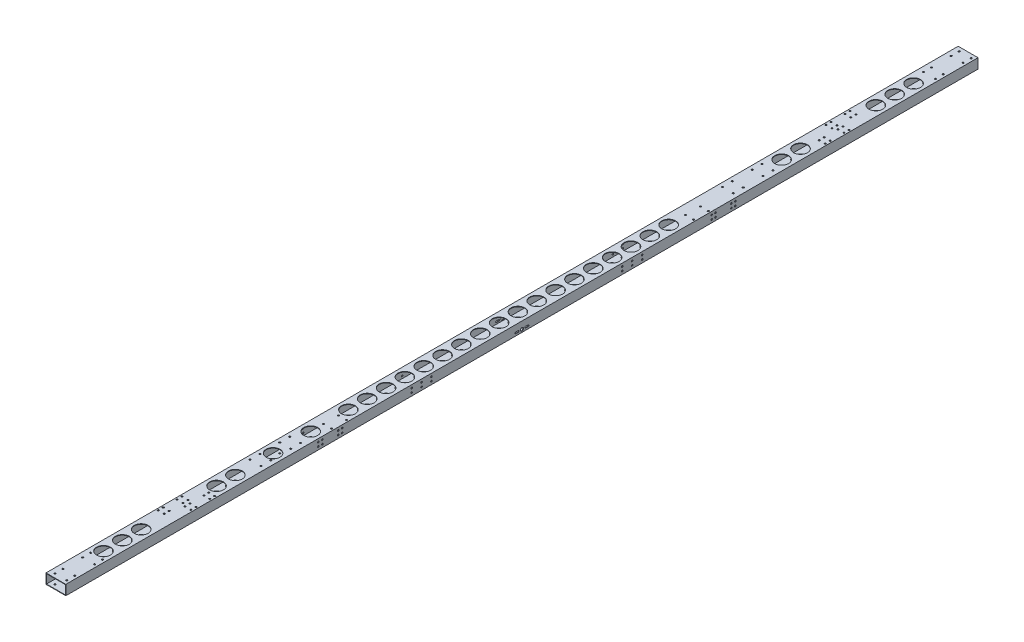
SolidWorks part; units mm, degrees
material "1100-H18 棒材(SS)"
ref_plane "前视基准面" through (0, 0, 0) normal (0, 0, 1) x (1, 0, 0)
ref_plane "上视基准面" through (0, 0, 0) normal (0, 1, 0) x (1, 0, 0)
ref_plane "右视基准面" through (0, 0, 0) normal (1, 0, 0) x (0, 0, -1)
other "Configuration Table"
sketch "草图1" plane through (0, 0, 0) normal (0, 0, 1) x (1, 0, 0)
  line L1 (0, 0) -> (40, 0)
  line L2 (0, 0) -> (0, 20)
  line L3 (0, 20) -> (40, 20)
  line L4 (40, 0) -> (40, 20)
  line L5 (1, 1) -> (39, 1)
  line L6 (1, 1) -> (1, 19)
  line L7 (1, 19) -> (39, 19)
  line L8 (39, 1) -> (39, 19)
  dimension "D1" = 40
  dimension "D2" = 20
  dimension "D3" = 1
  dimension "D4" = 1
  dimension "D5" = 1
  dimension "D6" = 1
extrude "凸台-拉伸1" add sketch "草图1" along normal blind 1840
sketch "草图2" plane through (0, 0, 0) normal (0, -1, 0) x (1, 0, 0)
  circle A9 centre (34, 8) radius 1.6
  circle A10 centre (34, 8) radius 1.6
  circle A11 centre (34, 24) radius 1.6
  circle A12 centre (34, 24) radius 1.6
  circle A13 centre (34, 64) radius 1.6
  circle A14 centre (34, 64) radius 1.6
  circle A15 centre (34, 80) radius 1.6
  circle A16 centre (34, 80) radius 1.6
  circle A17 centre (10, 64) radius 1.6
  circle A18 centre (10, 64) radius 1.6
  circle A19 centre (10, 80) radius 1.6
  circle A20 centre (10, 80) radius 1.6
  circle A21 centre (10, 24) radius 1.6
  circle A22 centre (10, 24) radius 1.6
  circle A23 centre (10, 8) radius 1.6
  circle A24 centre (10, 8) radius 1.6
  circle A39 centre (4, 232.5064) radius 1.6
  circle A40 centre (4, 232.5064) radius 1.6
  circle A41 centre (16, 270.5064) radius 1.6
  circle A42 centre (16, 270.5064) radius 1.6
  circle A43 centre (4, 270.5064) radius 1.6
  circle A44 centre (4, 270.5064) radius 1.6
  circle A45 centre (16, 222.5064) radius 1.6
  circle A46 centre (16, 222.5064) radius 1.6
  circle A47 centre (4, 222.5064) radius 1.6
  circle A48 centre (4, 222.5064) radius 1.6
  circle A49 centre (16, 260.5064) radius 1.6
  circle A50 centre (16, 260.5064) radius 1.6
  circle A51 centre (4, 260.5064) radius 1.6
  circle A52 centre (4, 260.5064) radius 1.6
  circle A53 centre (16, 232.5064) radius 1.6
  circle A54 centre (16, 232.5064) radius 1.6
  circle A61 centre (8, 483.5) radius 1.6
  circle A62 centre (8, 483.5) radius 1.6
  circle A63 centre (30, 483.5) radius 1.6
  circle A64 centre (30, 483.5) radius 1.6
  circle A65 centre (30, 463.5) radius 1.6
  circle A66 centre (30, 463.5) radius 1.6
  circle A67 centre (30, 423.5) radius 1.6
  circle A68 centre (30, 423.5) radius 1.6
  circle A69 centre (8, 403.5) radius 1.6
  circle A70 centre (8, 403.5) radius 1.6
  circle A71 centre (30, 403.5) radius 1.6
  circle A72 centre (30, 403.5) radius 1.6
  circle A75 centre (8, 423.5) radius 1.6
  circle A76 centre (8, 423.5) radius 1.6
  circle A77 centre (8, 463.5) radius 1.6
  circle A78 centre (8, 463.5) radius 1.6
  circle A81 centre (8, 1436.5) radius 1.6
  circle A82 centre (8, 1436.5) radius 1.6
  circle A83 centre (30, 1436.5) radius 1.6
  circle A84 centre (30, 1436.5) radius 1.6
  circle A85 centre (30, 1416.5) radius 1.6
  circle A86 centre (30, 1416.5) radius 1.6
  circle A87 centre (30, 1376.5) radius 1.6
  circle A88 centre (30, 1376.5) radius 1.6
  circle A89 centre (8, 1356.5) radius 1.6
  circle A90 centre (8, 1356.5) radius 1.6
  circle A91 centre (30, 1356.5) radius 1.6
  circle A92 centre (30, 1356.5) radius 1.6
  circle A95 centre (8, 1376.5) radius 1.6
  circle A96 centre (8, 1376.5) radius 1.6
  circle A97 centre (8, 1416.5) radius 1.6
  circle A98 centre (8, 1416.5) radius 1.6
  circle A103 centre (4, 1607.4936) radius 1.6
  circle A104 centre (4, 1607.4936) radius 1.6
  circle A105 centre (16, 1569.4936) radius 1.6
  circle A106 centre (16, 1569.4936) radius 1.6
  circle A107 centre (4, 1569.4936) radius 1.6
  circle A108 centre (4, 1569.4936) radius 1.6
  circle A109 centre (16, 1617.4936) radius 1.6
  circle A110 centre (16, 1617.4936) radius 1.6
  circle A111 centre (4, 1617.4936) radius 1.6
  circle A112 centre (4, 1617.4936) radius 1.6
  circle A113 centre (16, 1579.4936) radius 1.6
  circle A114 centre (16, 1579.4936) radius 1.6
  circle A115 centre (4, 1579.4936) radius 1.6
  circle A116 centre (4, 1579.4936) radius 1.6
  circle A117 centre (16, 1607.4936) radius 1.6
  circle A118 centre (16, 1607.4936) radius 1.6
  circle A127 centre (34, 1832) radius 1.6
  circle A128 centre (34, 1832) radius 1.6
  circle A129 centre (34, 1816) radius 1.6
  circle A130 centre (34, 1816) radius 1.6
  circle A131 centre (34, 1776) radius 1.6
  circle A132 centre (34, 1776) radius 1.6
  circle A133 centre (34, 1760) radius 1.6
  circle A134 centre (34, 1760) radius 1.6
  circle A135 centre (10, 1776) radius 1.6
  circle A136 centre (10, 1776) radius 1.6
  circle A137 centre (10, 1760) radius 1.6
  circle A138 centre (10, 1760) radius 1.6
  circle A139 centre (10, 1816) radius 1.6
  circle A140 centre (10, 1816) radius 1.6
  circle A141 centre (10, 1832) radius 1.6
  circle A142 centre (10, 1832) radius 1.6
  dimension "D5" = 0
  dimension "D6" = 0
  dimension "D7" = 0
  dimension "D8" = 0
  dimension "D9" = 0
  dimension "D10" = 0
  dimension "D11" = 0
  dimension "D12" = 0
  dimension "D14" = 0
  dimension "D15" = 0
  dimension "D16" = 0
  dimension "D17" = 0
  dimension "D18" = 0
  dimension "D19" = 0
  dimension "D20" = 0
  dimension "D21" = 0
  dimension "D22" = 0
  dimension "D23" = 0
  dimension "D24" = 0
  dimension "D25" = 0
  dimension "D26" = 0
  dimension "D27" = 0
  dimension "D29" = 0
  dimension "D30" = 0
  dimension "D31" = 0
  dimension "D32" = 0
  dimension "D33" = 0
  dimension "D34" = 0
  dimension "D35" = 0
  dimension "D36" = 0
  dimension "D38" = 0
  dimension "D39" = 0
  dimension "D40" = 0
  dimension "D41" = 0
  dimension "D42" = 0
  dimension "D43" = 0
  dimension "D44" = 0
  dimension "D45" = 0
  dimension "D46" = 0
  dimension "D47" = 0
  dimension "D49" = 0
  dimension "D50" = 0
  dimension "D51" = 0
  dimension "D52" = 0
  dimension "D53" = 0
  dimension "D54" = 0
  dimension "D55" = 0
  dimension "D56" = 0
extrude "切除-拉伸1" cut sketch "草图2" against normal through all
sketch "草图3" plane through (0, 0, 0) normal (0, -1, 0) x (1, 0, 0)
  line L0 (40, 1840) -> (40, 0) construction
  line L1 (20, 540) -> (36, 540) construction
  line L10 (20, 540) -> (20, 570) construction
  line L11 (20, 570) -> (36, 570) construction
  line L12 (36, 540) -> (36, 570) construction
  line L13 (40, 0) -> (0, 0) construction
  line L14 (40, 1840) -> (0, 1840) construction
  line L15 (20, 1270) -> (36, 1270) construction
  line L16 (20, 1270) -> (20, 1300) construction
  line L17 (20, 1300) -> (36, 1300) construction
  line L18 (36, 1270) -> (36, 1300) construction
  circle A0 centre (20, 1270) radius 1.6
  circle A1 centre (20, 1300) radius 1.6
  circle A5 centre (36, 1300) radius 1.6
  circle A9 centre (36, 294.2949) radius 1.6
  circle A10 centre (36, 294.2949) radius 1.6
  circle A11 centre (24, 256.2949) radius 1.6
  circle A12 centre (24, 256.2949) radius 1.6
  circle A13 centre (36, 256.2949) radius 1.6
  circle A14 centre (36, 256.2949) radius 1.6
  circle A15 centre (24, 304.2949) radius 1.6
  circle A16 centre (24, 304.2949) radius 1.6
  circle A17 centre (36, 304.2949) radius 1.6
  circle A18 centre (36, 304.2949) radius 1.6
  circle A19 centre (24, 266.2949) radius 1.6
  circle A20 centre (24, 266.2949) radius 1.6
  circle A21 centre (36, 266.2949) radius 1.6
  circle A22 centre (36, 266.2949) radius 1.6
  circle A23 centre (24, 294.2949) radius 1.6
  circle A24 centre (24, 294.2949) radius 1.6
  circle A25 centre (36, 1270) radius 1.6
  circle A31 centre (20, 540) radius 1.6
  circle A33 centre (36, 1545.7051) radius 1.6
  circle A34 centre (36, 1545.7051) radius 1.6
  circle A35 centre (24, 1583.7051) radius 1.6
  circle A36 centre (24, 1583.7051) radius 1.6
  circle A37 centre (36, 1583.7051) radius 1.6
  circle A38 centre (36, 1583.7051) radius 1.6
  circle A39 centre (24, 1535.7051) radius 1.6
  circle A40 centre (24, 1535.7051) radius 1.6
  circle A41 centre (36, 1535.7051) radius 1.6
  circle A42 centre (36, 1535.7051) radius 1.6
  circle A43 centre (24, 1573.7051) radius 1.6
  circle A44 centre (24, 1573.7051) radius 1.6
  circle A45 centre (36, 1573.7051) radius 1.6
  circle A46 centre (36, 1573.7051) radius 1.6
  circle A47 centre (24, 1545.7051) radius 1.6
  circle A48 centre (24, 1545.7051) radius 1.6
  circle A49 centre (36, 540) radius 1.6
  circle A54 centre (20, 570) radius 1.6
  circle A55 centre (36, 570) radius 1.6
  dimension "D27" = 3.2
  dimension "D28" = 3.2
  dimension "D3" = 30
  dimension "D4" = 16
  dimension "D13" = 4
  dimension "D22" = 540
  dimension "D23" = 30
  dimension "D24" = 16
  dimension "D25" = 4
  dimension "D26" = 540
  dimension "D5" = 0
  dimension "D6" = 0
  dimension "D7" = 0
  dimension "D8" = 0
  dimension "D9" = 0
  dimension "D10" = 0
  dimension "D11" = 0
  dimension "D12" = 0
  dimension "D14" = 0
  dimension "D15" = 0
  dimension "D16" = 0
  dimension "D17" = 0
  dimension "D18" = 0
  dimension "D19" = 0
  dimension "D20" = 0
  dimension "D21" = 0
extrude "切除-拉伸2" cut sketch "草图3" against normal through all
sketch "草图4" plane through (40, 0, 0) normal (1, 0, 0) x (0, 0, -1)
  line L2 (-907.5, 7) -> (-912.5, 7)
  line L3 (-912.5, 4) -> (-907.5, 4)
  line L4 (-907.5, 7) -> (-912.5, 7)
  line L5 (-912.5, 4) -> (-907.5, 4)
  line L6 (-927.5, 7) -> (-932.5, 7)
  line L7 (-932.5, 4) -> (-927.5, 4)
  line L8 (-927.5, 7) -> (-932.5, 7)
  line L9 (-932.5, 4) -> (-927.5, 4)
  circle A0 centre (-920, 5.5) radius 3.1
  circle A1 centre (-920, 5.5) radius 3
  circle A2 centre (-920, 5.5) radius 3 construction
  arc A4 (-912.5, 7) -> (-912.5, 4) centre (-912.5, 5.5) ccw
  arc A5 (-907.5, 4) -> (-907.5, 7) centre (-907.5, 5.5) ccw
  arc A6 (-912.5, 7) -> (-912.5, 4) centre (-912.5, 5.5) ccw
  arc A7 (-907.5, 4) -> (-907.5, 7) centre (-907.5, 5.5) ccw
  arc A8 (-932.5, 7) -> (-932.5, 4) centre (-932.5, 5.5) ccw
  arc A9 (-927.5, 4) -> (-927.5, 7) centre (-927.5, 5.5) ccw
  arc A10 (-932.5, 7) -> (-932.5, 4) centre (-932.5, 5.5) ccw
  arc A11 (-927.5, 4) -> (-927.5, 7) centre (-927.5, 5.5) ccw
  dimension "D4" = 6.2
  dimension "D1" = 0
  dimension "D2" = 0
  dimension "D3" = 0
extrude "切除-拉伸3" cut sketch "草图4" against normal through all
sketch "草图5" plane through (0, 0, 0) normal (-1, 0, 0) x (0, 0, 1)
  circle A0 centre (557.5, 14) radius 1.6 [skipped]
  circle A1 centre (557.5, 6) radius 1.6 [skipped]
  circle A5 centre (577.5, 14) radius 1.6 [skipped]
  circle A9 centre (537.5, 6) radius 1.6
  circle A10 centre (537.5, 6) radius 1.6
  circle A11 centre (537.5, 14) radius 1.6
  circle A12 centre (537.5, 14) radius 1.6
  circle A13 centre (497.5, 6) radius 1.6
  circle A14 centre (497.5, 6) radius 1.6
  circle A15 centre (497.5, 14) radius 1.6
  circle A16 centre (497.5, 14) radius 1.6
  circle A17 centre (489.5, 6) radius 1.6
  circle A18 centre (489.5, 6) radius 1.6
  circle A19 centre (489.5, 14) radius 1.6
  circle A20 centre (489.5, 14) radius 1.6
  circle A21 centre (529.5, 14) radius 1.6
  circle A22 centre (529.5, 14) radius 1.6
  circle A23 centre (529.5, 6) radius 1.6
  circle A24 centre (529.5, 6) radius 1.6
  circle A25 centre (577.5, 6) radius 1.6 [skipped]
  circle A27 centre (597.5, 14) radius 1.6 [skipped]
  circle A29 centre (1282.5, 6) radius 1.6
  circle A30 centre (1282.5, 6) radius 1.6
  circle A31 centre (1282.5, 14) radius 1.6
  circle A32 centre (1282.5, 14) radius 1.6
  circle A33 centre (1322.5, 6) radius 1.6
  circle A34 centre (1322.5, 6) radius 1.6
  circle A35 centre (1322.5, 14) radius 1.6
  circle A36 centre (1322.5, 14) radius 1.6
  circle A37 centre (1330.5, 6) radius 1.6
  circle A38 centre (1330.5, 6) radius 1.6
  circle A39 centre (1330.5, 14) radius 1.6
  circle A40 centre (1330.5, 14) radius 1.6
  circle A41 centre (1290.5, 14) radius 1.6
  circle A42 centre (1290.5, 14) radius 1.6
  circle A43 centre (1290.5, 6) radius 1.6
  circle A44 centre (1290.5, 6) radius 1.6
  circle A45 centre (597.5, 6) radius 1.6 [skipped]
  circle A46 centre (617.5, 14) radius 1.6 [skipped]
  circle A47 centre (617.5, 6) radius 1.6 [skipped]
  circle A48 centre (637.5, 14) radius 1.6 [skipped]
  circle A49 centre (637.5, 6) radius 1.6 [skipped]
  circle A50 centre (657.5, 14) radius 1.6 [skipped]
  circle A51 centre (657.5, 6) radius 1.6 [skipped]
  circle A52 centre (677.5, 14) radius 1.6
  circle A53 centre (677.5, 6) radius 1.6
  circle A54 centre (697.5, 14) radius 1.6
  circle A55 centre (697.5, 6) radius 1.6
  circle A56 centre (717.5, 14) radius 1.6
  circle A57 centre (717.5, 6) radius 1.6
  circle A58 centre (1262.5, 14) radius 1.6 [skipped]
  circle A59 centre (1262.5, 6) radius 1.6 [skipped]
  circle A60 centre (1242.5, 14) radius 1.6 [skipped]
  circle A61 centre (1242.5, 6) radius 1.6 [skipped]
  circle A62 centre (1222.5, 14) radius 1.6 [skipped]
  circle A63 centre (1222.5, 6) radius 1.6 [skipped]
  circle A64 centre (1202.5, 14) radius 1.6 [skipped]
  circle A65 centre (1202.5, 6) radius 1.6 [skipped]
  circle A66 centre (1182.5, 14) radius 1.6 [skipped]
  circle A67 centre (1182.5, 6) radius 1.6 [skipped]
  circle A68 centre (1162.5, 14) radius 1.6 [skipped]
  circle A69 centre (1162.5, 6) radius 1.6 [skipped]
  circle A70 centre (1142.5, 14) radius 1.6
  circle A71 centre (1142.5, 6) radius 1.6
  circle A72 centre (1122.5, 14) radius 1.6
  circle A73 centre (1122.5, 6) radius 1.6
  circle A74 centre (1102.5, 14) radius 1.6
  circle A75 centre (1102.5, 6) radius 1.6
  dimension "D13" = 140
  dimension "D22" = 140
  dimension "D3" = 10
  dimension "D4" = 10
  dimension "D5" = 0
  dimension "D6" = 0
  dimension "D7" = 0
  dimension "D8" = 0
  dimension "D9" = 0
  dimension "D10" = 0
  dimension "D11" = 0
  dimension "D12" = 0
  dimension "D14" = 0
  dimension "D15" = 0
  dimension "D16" = 0
  dimension "D17" = 0
  dimension "D18" = 0
  dimension "D19" = 0
  dimension "D20" = 0
  dimension "D21" = 0
extrude "切除-拉伸4" cut sketch "草图5" against normal through all
sketch "草图6" plane through (0, 20, 0) normal (0, 1, 0) x (1, 0, 0)
  line L0 (40, -1840) -> (40, 0) construction
  line L1 (40, 0) -> (0, 0) construction
  circle A0 centre (20, -110) radius 14
  circle A1 centre (20, -148) radius 14
  circle A2 centre (20, -186) radius 14
  circle A3 centre (20, -224) radius 14 [skipped]
  circle A4 centre (20, -262) radius 14 [skipped]
  circle A5 centre (20, -300) radius 14 [skipped]
  circle A6 centre (20, -338) radius 14
  circle A7 centre (20, -376) radius 14
  circle A8 centre (20, -414) radius 14 [skipped]
  circle A9 centre (20, -452) radius 14 [skipped]
  circle A10 centre (20, -490) radius 14 [skipped]
  circle A11 centre (20, -528) radius 14 [skipped]
  circle A12 centre (20, -566) radius 14 [skipped]
  circle A13 centre (20, -604) radius 14
  circle A14 centre (20, -642) radius 14
  circle A15 centre (20, -680) radius 14
  circle A16 centre (20, -718) radius 14
  circle A17 centre (20, -756) radius 14
  circle A18 centre (20, -794) radius 14
  circle A19 centre (20, -832) radius 14
  circle A20 centre (20, -870) radius 14
  circle A21 centre (20, -908) radius 14
  circle A22 centre (20, -946) radius 14
  circle A23 centre (20, -984) radius 14
  circle A24 centre (20, -1022) radius 14
  circle A25 centre (20, -1060) radius 14
  circle A26 centre (20, -1098) radius 14
  circle A27 centre (20, -1136) radius 14
  circle A28 centre (20, -1174) radius 14
  circle A29 centre (20, -1212) radius 14
  circle A30 centre (20, -1250) radius 14
  circle A31 centre (20, -1288) radius 14 [skipped]
  circle A32 centre (20, -1326) radius 14
  circle A33 centre (20, -1364) radius 14 [skipped]
  circle A34 centre (20, -1402) radius 14
  circle A35 centre (20, -1440) radius 14 [skipped]
  circle A36 centre (20, -1478) radius 14
  circle A37 centre (20, -1516) radius 14
  circle A38 centre (20, -1554) radius 14 [skipped]
  circle A39 centre (20, -1592) radius 14 [skipped]
  circle A40 centre (20, -1630) radius 14 [skipped]
  circle A41 centre (20, -1668) radius 14
  circle A42 centre (20, -1706) radius 14
  circle A43 centre (20, -1744) radius 14
  circle A44 centre (20, -1782) radius 14 [skipped]
  dimension "D1" = 28
  dimension "D5" = 38
  dimension "D2" = 20
  dimension "D3" = 110
  dimension "D4" = 45
extrude "切除-拉伸5" cut sketch "草图6" against normal through all
